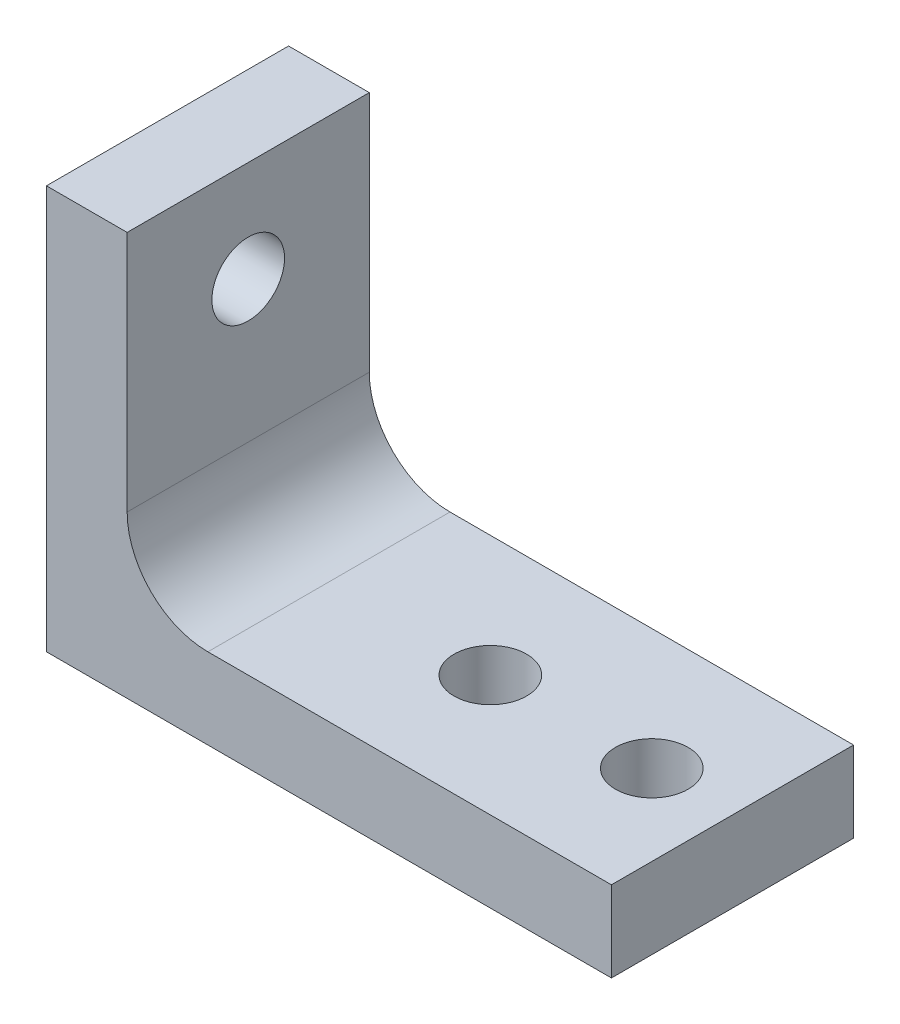
SolidWorks part; units mm, degrees
ref_plane "Front Plane" through (0, 0, 0) normal (0, 0, 1) x (1, 0, 0)
ref_plane "Top Plane" through (0, 0, 0) normal (0, 1, 0) x (1, 0, 0)
ref_plane "Right Plane" through (0, 0, 0) normal (1, 0, 0) x (0, 0, -1)
sketch "Sketch1" plane through (0, 0, 0) normal (0, 0, 1) x (1, 0, 0)
  line L0 (0, 0) -> (0, 40)
  line L1 (0, 40) -> (-10, 40)
  line L2 (-10, 40) -> (-10, -10)
  line L3 (-10, -10) -> (10, -10)
  line L4 (10, -10) -> (60, -10)
  line L5 (60, -10) -> (60, 0)
  line L6 (60, 0) -> (0, 0)
  dimension "D1" = 10
  dimension "D2" = 60
  dimension "D3" = 10
  dimension "D4" = 50
extrude "Boss-Extrude1" add sketch "Sketch1" along normal blind 30
hole_wizard "M8 Clearance Hole1" positions "Sketch2" profile "Sketch3" hole size "M8" standard "ANSI Metric" end condition through all
sketch "Sketch2" plane through (0, 0, 0) normal (1, 0, 0) x (0, 0, -1)
  line L0 (-30, -10) -> (0, -10) construction
  line L1 (-30, 40) -> (0, 40) construction
  point P0 (-15, 27.5)
  point P3 (0, 0)
  point P6 (0, 0)
  point P9 (-15, 40)
  dimension "D1" = 37.5
sketch "Sketch3" plane through (0, 27.5, 15) normal (0, 1, 0) x (0, 0, -1)
  line L0 (0, 0) -> (0, 10)
  line L1 (0, 10) -> (4.5, 10)
  line L2 (4.5, 10) -> (4.5, 0)
  line L5 (4.5, 0) -> (0, 0)
  line L11 (0, -6.35) -> (0, 107.95) construction
  dimension "Thru Hole Dia." = 9
  dimension "Thru Hole Depth" = 10
hole_wizard "M8 Clearance Hole2" positions "Sketch4" profile "Sketch5" hole size "M8" standard "ANSI Metric" end condition through all
sketch "Sketch4" plane through (0, 0, 0) normal (0, 1, 0) x (1, 0, 0)
  line L2 (60, -30) -> (60, 0) construction
  line L3 (60, -15) -> (50, -15) construction
  line L4 (50, -15) -> (30, -15) construction
  point P0 (30, -15)
  point P9 (50, -15)
  point P15 (60, -15)
  dimension "D1" = 10
  dimension "D2" = 20
sketch "Sketch5" plane through (30, 0, 15) normal (1, 0, 0) x (0, 0, 1)
  line L0 (0, 0) -> (0, 10)
  line L1 (0, 10) -> (4.5, 10)
  line L2 (4.5, 10) -> (4.5, 0)
  line L5 (4.5, 0) -> (0, 0)
  line L11 (0, -6.35) -> (0, 107.95) construction
  dimension "Thru Hole Dia." = 9
  dimension "Thru Hole Depth" = 10
fillet "Fillet1" radius 10 1 edges at (0, 0, 15)
